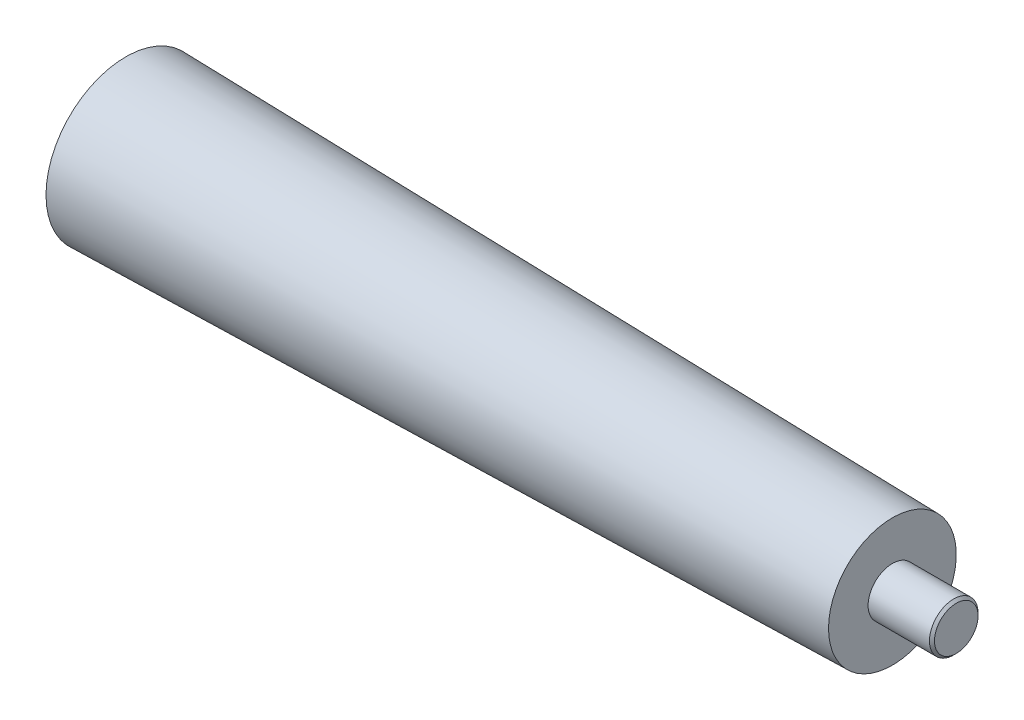
SolidWorks part; units mm, degrees
ref_plane "Front Plane" through (0, 0, 0) normal (0, 0, 1) x (1, 0, 0)
ref_plane "Top Plane" through (0, 0, 0) normal (0, 1, 0) x (1, 0, 0)
ref_plane "Right Plane" through (0, 0, 0) normal (1, 0, 0) x (0, 0, -1)
sketch "Sketch1" plane through (0, 0, 0) normal (0, 1, 0) x (1, 0, 0)
  line L0 (0, 0) -> (165.1, 0)
  line L1 (165.1, 0) -> (165.1, 4.83)
  line L2 (165.1, 4.83) -> (152.4, 4.83)
  line L3 (152.4, 4.83) -> (152.4, 12.7)
  line L4 (152.4, 12.7) -> (0, 15.88)
  line L5 (0, 15.88) -> (0, 0)
  point P3 (152.4, 8.765)
  dimension "D1" = 12.7
  dimension "D2" = 12.7
  dimension "D3" = 4.83
  dimension "D4" = 152.4
  dimension "D5" = 15.88
revolve "Revolve1" add sketch "Sketch1" angle 360 about L0
chamfer "Chamfer1" distance 0.5 angle 45 1 edges at (165.1, 0, 4.83)
